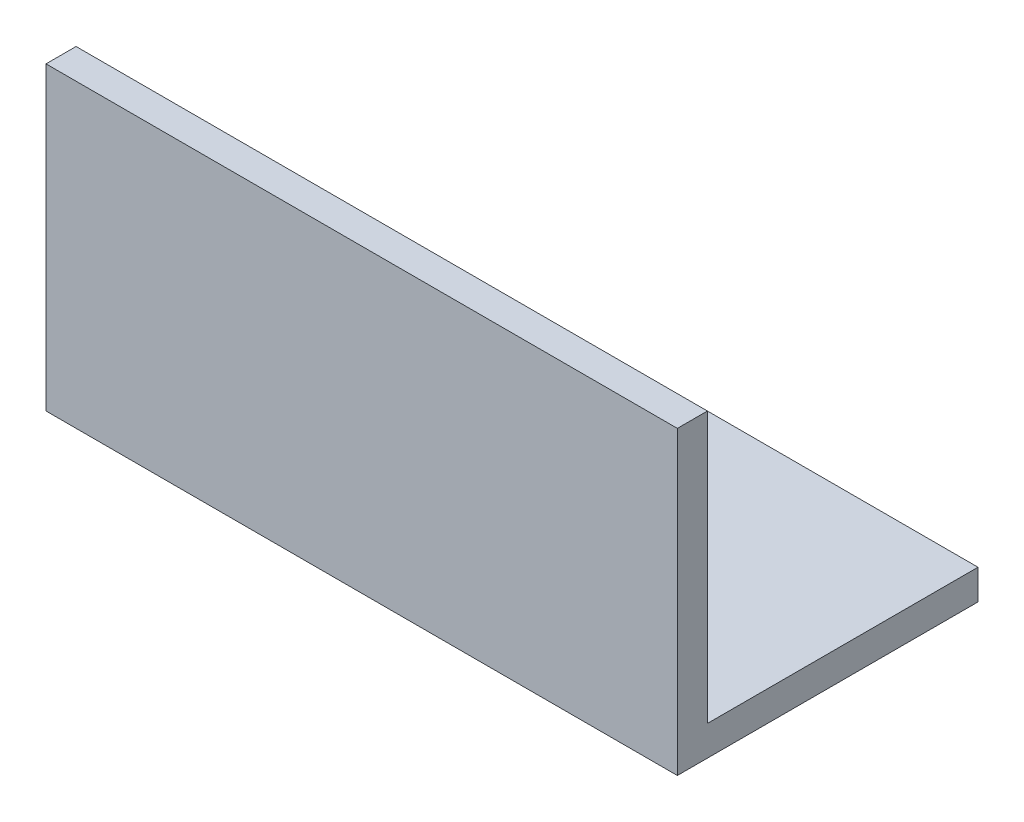
SolidWorks part; units mm, degrees
ref_plane "Front Plane" through (0, 0, 0) normal (0, 0, 1) x (1, 0, 0)
ref_plane "Top Plane" through (0, 0, 0) normal (0, 1, 0) x (1, 0, 0)
ref_plane "Right Plane" through (0, 0, 0) normal (1, 0, 0) x (0, 0, -1)
sketch "Sketch1" plane through (0, 0, 0) normal (1, 0, 0) x (0, 0, -1)
  line L0 (0, 20) -> (0, 0)
  line L1 (0, 0) -> (20, 0)
  line L2 (20, 0) -> (20, 2)
  line L3 (20, 2) -> (2, 2)
  line L4 (2, 2) -> (2, 20)
  line L5 (2, 20) -> (0, 20)
  dimension "D1" = 20
  dimension "D2" = 20
  dimension "D3" = 2
  dimension "D4" = 2
extrude "Boss-Extrude1" add sketch "Sketch1" against normal blind 42
sketch "Sketch2" plane through (0, 2, 0) normal (0, 1, 0) x (1, 0, 0)
  line L0 (-42, 20) -> (0, 2) construction
  line L1 (-42, 2) -> (0, 20) construction
  line L2 (-21, 11) -> (-21, 15.2619) construction
  circle A0 centre (-21, 15.2619) radius 1.2645
  circle A1 centre (-16.7381, 11) radius 1.2645
  circle A2 centre (-21, 6.7381) radius 1.2645
  circle A3 centre (-25.2619, 11) radius 1.2645
  point P11 (-1.7992, -7.4905)
  point P12 (-21, 11)
  point P20 (-21, 11)
  dimension "D1" = 2.529
  dimension "D2" = 4.2619
  dimension "D3" = 4
extrude "Cut-Extrude1" cut sketch "Sketch2" against normal through all
